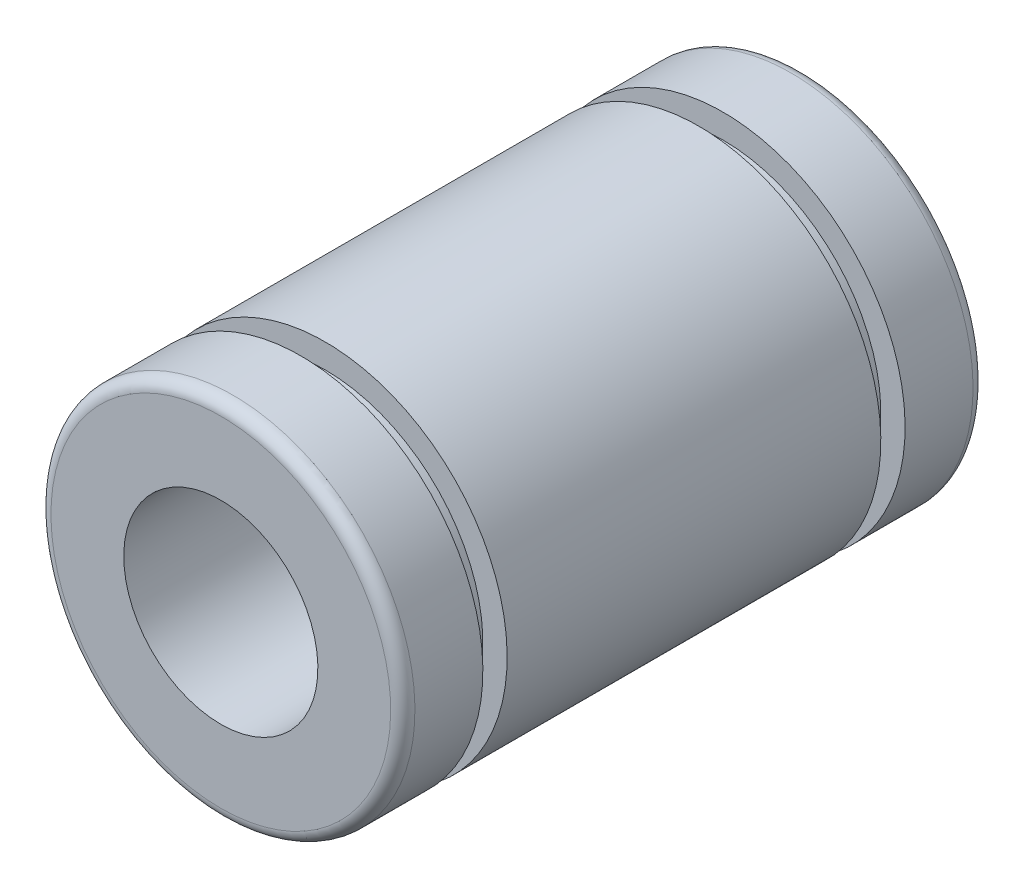
SolidWorks part; units mm, degrees
ref_plane "Спереди" through (0, 0, 0) normal (0, 0, 1) x (1, 0, 0)
ref_plane "Сверху" through (0, 0, 0) normal (0, 1, 0) x (1, 0, 0)
ref_plane "Справа" through (0, 0, 0) normal (1, 0, 0) x (0, 0, -1)
sketch "Эскиз2" plane through (0, 0, 0) normal (1, 0, 0) x (0, 0, -1)
  line L0 (-89.0417, 0) -> (34.5275, 0) construction
  line L1 (7.7, -6.5) -> (7.7, -7.5)
  line L2 (-12, 0) -> (-12, -7)
  line L3 (-11.5, -7.5) -> (-8.7, -7.5)
  line L4 (-8.7, -7.5) -> (-8.7, -6.5)
  line L5 (-8.7, -6.5) -> (-7.7, -6.5)
  line L6 (-7.7, -6.5) -> (-7.7, -7.5)
  line L7 (-7.7, -7.5) -> (7.7, -7.5)
  line L8 (0, -7.5) -> (0, 0) construction
  line L9 (-12, 0) -> (12, 0)
  line L10 (0, 0) -> (0, -7.5)
  line L11 (8.7, -6.5) -> (7.7, -6.5)
  line L12 (8.7, -7.5) -> (8.7, -6.5)
  line L13 (11.5, -7.5) -> (8.7, -7.5)
  line L14 (12, 0) -> (12, -7)
  line L15 (-12, -4) -> (12, -4)
  arc A0 (12, -7) -> (11.5, -7.5) centre (11.5, -7) cw
  arc A1 (-11.5, -7.5) -> (-12, -7) centre (-11.5, -7) cw
  point P21 (12, -7.5)
  point P24 (-12, -7.5)
  dimension "D6" = 0.5
  dimension "D1" = 1
  dimension "D2" = 3.3
  dimension "D3" = 12
  dimension "D5" = 4
  dimension "D7" = 7.5
revolve "Повернуть1" add sketch "Эскиз2" angle 360 about L9
